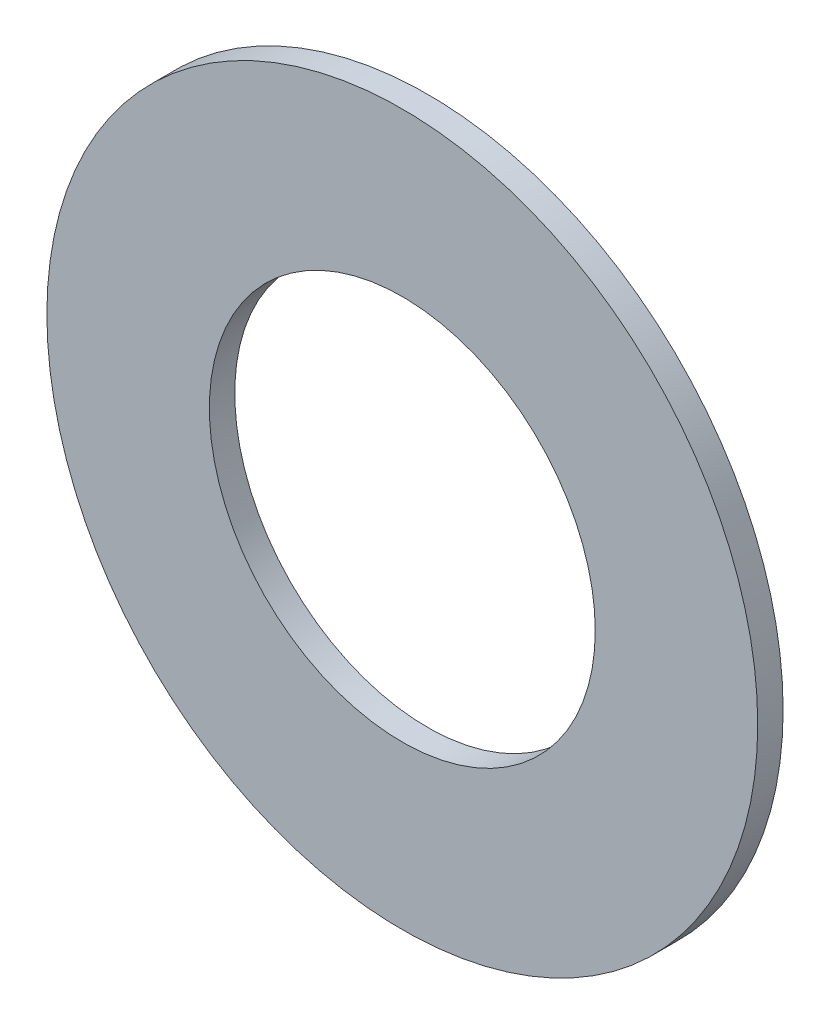
SolidWorks part; units mm, degrees
ref_plane "前视基准面" through (0, 0, 0) normal (0, 0, 1) x (1, 0, 0)
ref_plane "上视基准面" through (0, 0, 0) normal (0, 1, 0) x (1, 0, 0)
ref_plane "右视基准面" through (0, 0, 0) normal (1, 0, 0) x (0, 0, -1)
other "Configuration Table"
sketch "草图1" plane through (0, 0, 0) normal (0, 0, 1) x (1, 0, 0)
  circle A0 centre (0, 0) radius 14
  circle A1 centre (0, 0) radius 7.6
  dimension "D1" = 15.2
  dimension "D2" = 28
extrude "凸台-拉伸1" add sketch "草图1" along normal blind 1
